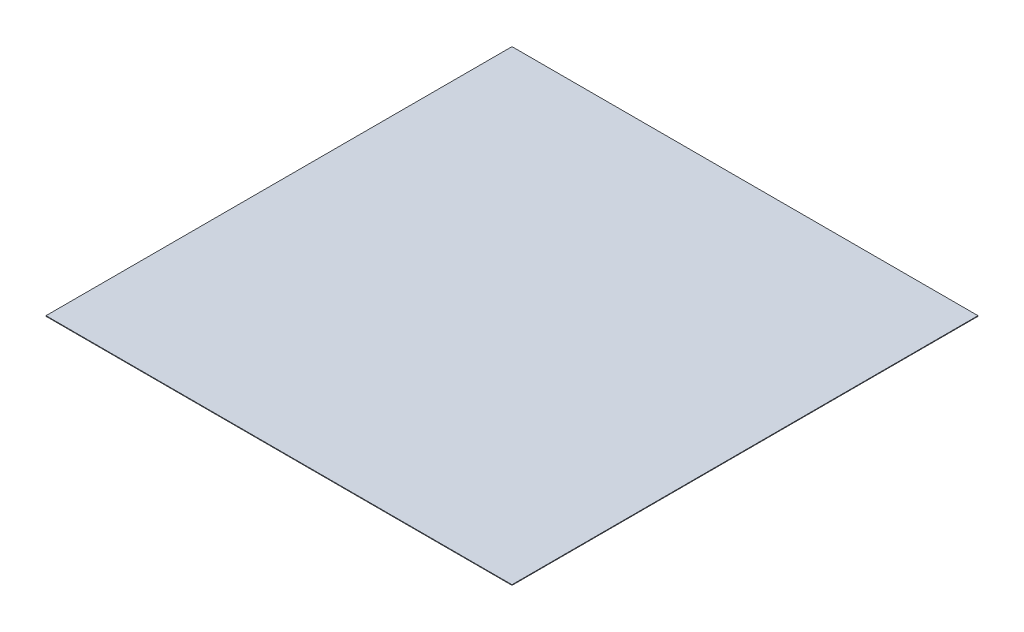
SolidWorks part; units mm, degrees
material "6061-T6 (SS)"
ref_plane "Front" through (0, 0, 0) normal (0, 0, 1) x (1, 0, 0)
ref_plane "Top" through (0, 0, 0) normal (0, 1, 0) x (1, 0, 0)
ref_plane "Right" through (0, 0, 0) normal (1, 0, 0) x (0, 0, -1)
sketch "Sketch1" plane through (0, 0, 0) normal (0, 1, 0) x (1, 0, 0)
  line L1 (0, 0) -> (3310, 0)
  line L2 (0, 0) -> (0, -3310)
  line L3 (0, -3310) -> (3310, -3310)
  line L4 (3310, 0) -> (3310, -3310)
  dimension "D1" = 3310
  dimension "D2" = 3310
extrude "Boss-Extrude1" add sketch "Sketch1" along normal blind 4.2333
